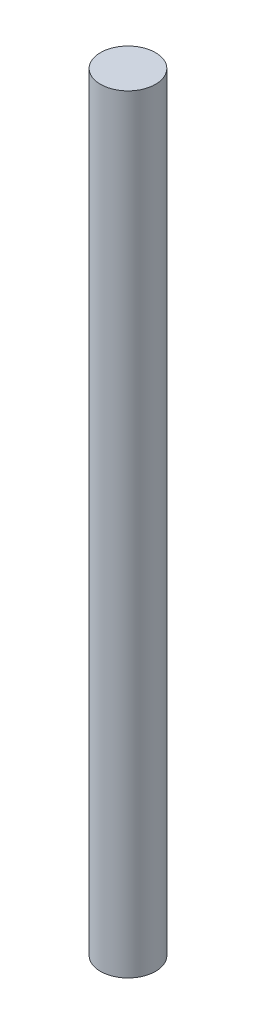
SolidWorks part; units mm, degrees
ref_plane "Front Plane" through (0, 0, 0) normal (0, 0, 1) x (1, 0, 0)
ref_plane "Top Plane" through (0, 0, 0) normal (0, 1, 0) x (1, 0, 0)
ref_plane "Right Plane" through (0, 0, 0) normal (1, 0, 0) x (0, 0, -1)
sketch "Sketch1" plane through (0, 0, 0) normal (0, 1, 0) x (1, 0, 0)
  circle A0 centre (0, 0) radius 2.5
  dimension "D1" = 5
extrude "Boss-Extrude1" add sketch "Sketch1" along normal blind 69.85
